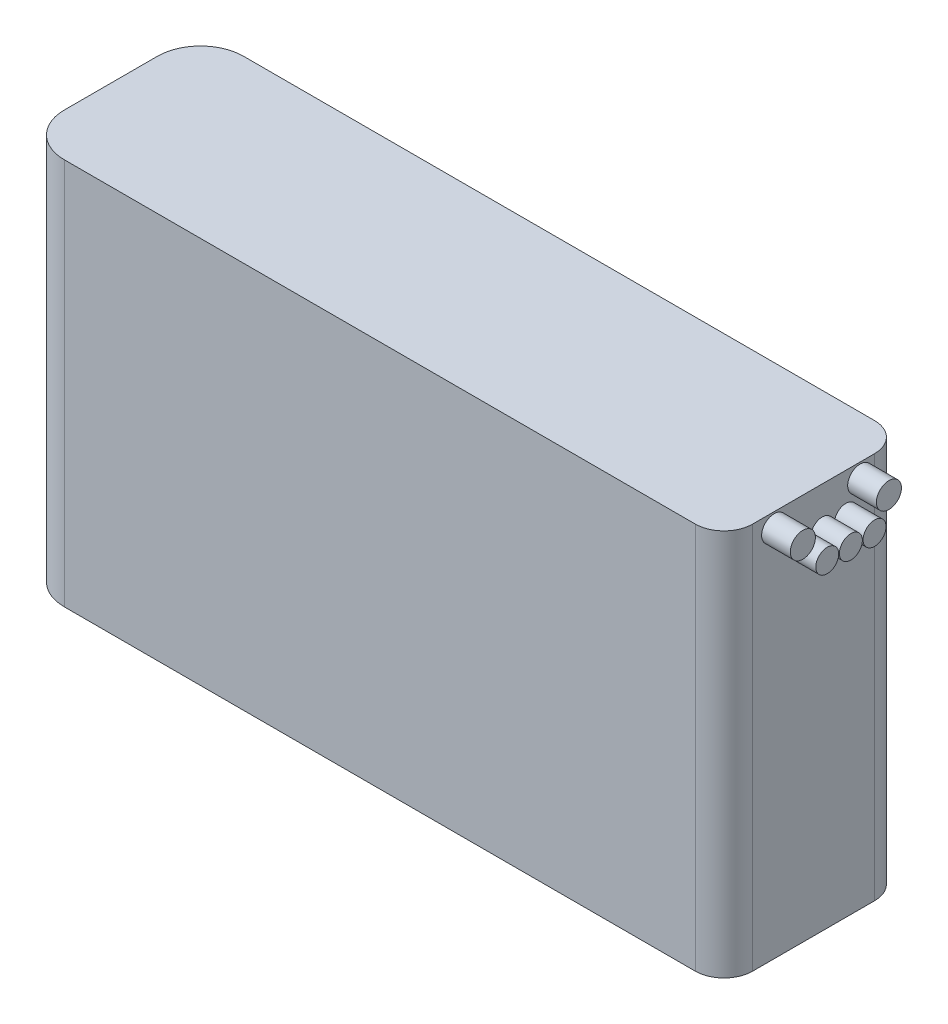
SolidWorks part; units mm, degrees
ref_plane "Ebene vorne" through (0, 0, 0) normal (0, 0, 1) x (1, 0, 0)
ref_plane "Ebene oben" through (0, 0, 0) normal (0, 1, 0) x (1, 0, 0)
ref_plane "Ebene rechts" through (0, 0, 0) normal (1, 0, 0) x (0, 0, -1)
sketch "Skizze1" plane through (0, 0, 0) normal (0, 0, 1) x (1, 0, 0)
  line L1 (0, 0) -> (49, 0)
  line L2 (0, 0) -> (0, 27)
  line L3 (0, 27) -> (49, 27)
  line L4 (49, 0) -> (49, 27)
  dimension "D1" = 49
  dimension "D2" = 27
extrude "Aufsatz-Linear austragen1" add sketch "Skizze1" along normal blind 12.5
fillet "Verrundung1" radius 2 2 edges at (49, 13.5, 0) (49, 13.5, 12.5)
fillet "Verrundung2" radius 3 2 edges at (0, 13.5, 12.5) (0, 13.5, 0)
sketch "Skizze3" plane through (49, 0, 0) normal (1, 0, 0) x (0, 0, -1)
  line L0 (-10.5, 27) -> (-2, 27) construction
  line L1 (0, 27) -> (0, 0) construction
  line L2 (-7.3, 24.2) -> (-5.65, 24.2) construction
  line L3 (-5.65, 24.2) -> (-4, 24.2) construction
  circle A0 centre (-9, 26) radius 0.875
  circle A1 centre (-3, 26) radius 0.875
  circle A2 centre (-4, 24.2) radius 0.8
  circle A3 centre (-5.65, 24.2) radius 0.8
  circle A4 centre (-7.3, 24.2) radius 0.8
  point P14 (-3, 23.9842)
  point P16 (0, 23.451)
  point P18 (0, 23.6107)
  dimension "D1" = 1.75
  dimension "D6" = 1.6
  dimension "D2" = 1
  dimension "D3" = 6
  dimension "D4" = 3
  dimension "D5" = 1.65
  dimension "D7" = 4
  dimension "D8" = 1.8
extrude "Aufsatz-Linear austragen2" add sketch "Skizze3" along normal blind 2
